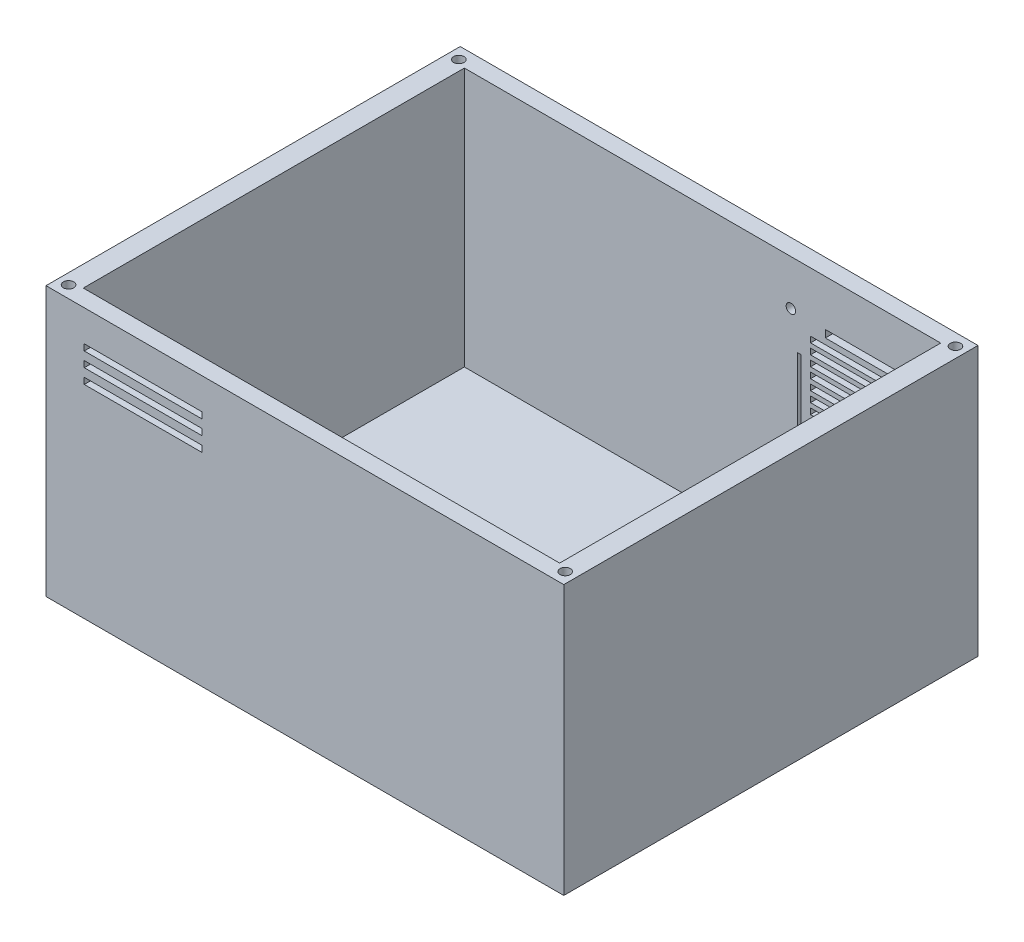
SolidWorks part; units mm, degrees
ref_plane "Front Plane" through (0, 0, 0) normal (0, 0, 1) x (1, 0, 0)
ref_plane "Top Plane" through (0, 0, 0) normal (0, 1, 0) x (1, 0, 0)
ref_plane "Right Plane" through (0, 0, 0) normal (1, 0, 0) x (0, 0, -1)
sketch "Sketch1" plane through (0, 0, 0) normal (0, 1, 0) x (1, 0, 0)
  line L1 (125, 100) -> (-125, 100)
  line L2 (125, 100) -> (125, -100)
  line L3 (125, -100) -> (-125, -100)
  line L4 (-125, 100) -> (-125, -100)
  line L5 (125, 100) -> (-125, -100) construction
  line L6 (125, -100) -> (-125, 100) construction
  line L7 (115, -92) -> (-115, -92)
  line L8 (115, -92) -> (115, 92)
  line L9 (115, 92) -> (-115, 92)
  line L10 (-115, -92) -> (-115, 92)
  line L11 (115, -92) -> (-115, 92) construction
  line L12 (115, 92) -> (-115, -92) construction
  point P0 (0, 0)
  point P6 (0, 0)
  dimension "D1" = 250
  dimension "D2" = 200
  dimension "D3" = 230
extrude "Boss-Extrude1" add sketch "Sketch1" along normal blind 125
sketch "Sketch2" plane through (0, 0, 0) normal (0, 1, 0) x (1, 0, 0)
  line L1 (-125, 100) -> (125, 100)
  line L2 (-125, 100) -> (-125, -100)
  line L3 (-125, -100) -> (125, -100)
  line L4 (125, 100) -> (125, -100)
extrude "Boss-Extrude2" add sketch "Sketch2" against normal blind 5
sketch "Sketch3" plane through (0, 125, 0) normal (0, 1, 0) x (1, 0, 0)
  line L0 (0, 0) -> (0, 92) construction
  line L1 (115, 92) -> (-115, 92) construction
  line L2 (0, 0) -> (-125, 0) construction
  line L3 (-125, 100) -> (-125, -100) construction
  circle A0 centre (-119.9007, -94.2189) radius 2.5
  circle A1 centre (-119.9007, 94.2189) radius 2.5
  circle A2 centre (119.9007, 94.2189) radius 2.5
  circle A3 centre (119.9007, -94.2189) radius 2.5
  dimension "D1" = 5
extrude "Cut-Extrude1" cut sketch "Sketch3" against normal blind 5
sketch "Sketch4" plane through (0, 0, 100) normal (0, 0, 1) x (1, 0, 0)
  line L1 (-106.5358, 109.9222) -> (-49.6477, 109.9222)
  line L2 (-106.5358, 109.9222) -> (-106.5358, 106.9222)
  line L3 (-106.5358, 106.9222) -> (-49.6477, 106.9222)
  line L4 (-49.6477, 109.9222) -> (-49.6477, 106.9222)
  line L5 (-106.5358, 102.9222) -> (-49.6477, 102.9222)
  line L6 (-106.5358, 102.9222) -> (-106.5358, 99.9222)
  line L7 (-106.5358, 99.9222) -> (-49.6477, 99.9222)
  line L8 (-49.6477, 102.9222) -> (-49.6477, 99.9222)
  line L9 (-106.5358, 95.9222) -> (-49.6477, 95.9222)
  line L10 (-106.5358, 95.9222) -> (-106.5358, 92.9222)
  line L11 (-106.5358, 92.9222) -> (-49.6477, 92.9222)
  line L12 (-49.6477, 95.9222) -> (-49.6477, 92.9222)
  dimension "D1" = 4
  dimension "D2" = 4
  dimension "D3" = 3
  dimension "D4" = 3
  dimension "D5" = 3
extrude "Cut-Extrude2" cut sketch "Sketch4" against normal blind 10
sketch "Sketch5" plane through (0, 0, -100) normal (0, 0, -1) x (-1, 0, 0)
  line L0 (-113.6581, 32.2575) -> (-42.6569, 103.2575) construction
  line L3 (-125, 67.7575) -> (125, 67.7575) construction
  line L4 (-125, 125) -> (-125, -5) construction
  line L5 (125, 125) -> (125, -5) construction
  circle A1 centre (-42.6569, 32.2575) radius 2.28
  circle A2 centre (-113.6581, 103.2575) radius 2.28
  circle A3 centre (-42.6569, 103.2575) radius 2.28
  circle A4 centre (-113.6581, 32.2575) radius 2.28
  point P0 (0, 0)
  dimension "D1" = 4.56
  dimension "D2" = 100.41
  dimension "D3" = 71
  dimension "D4" = 71
extrude "Cut-Extrude3" cut sketch "Sketch5" against normal blind 10
sketch "Sketch6" plane through (0, 0, -100) normal (0, 0, -1) x (-1, 0, 0)
  line L0 (-113.6581, 103.2575) -> (-42.6569, 32.2575) construction
  line L1 (-113.6581, 32.2575) -> (-42.6569, 103.2575) construction
  line L14 (-104.042, 88.6415) -> (-104.042, 91.4547)
  line L15 (-104.042, 93.6415) -> (-52.1185, 93.6415)
  line L16 (-104.042, 93.6415) -> (-104.042, 96.4547)
  line L17 (-104.042, 96.4547) -> (-52.1185, 96.4547)
  line L18 (-52.1185, 93.6415) -> (-52.1185, 96.4547)
  line L19 (-104.042, 88.6415) -> (-52.1185, 88.6415)
  line L20 (-52.1185, 88.6415) -> (-52.1185, 91.4547)
  line L21 (-104.042, 91.4547) -> (-52.1185, 91.4547)
  line L22 (-104.042, 83.6415) -> (-104.042, 86.4547)
  line L23 (-104.042, 83.6415) -> (-52.1185, 83.6415)
  line L24 (-52.1185, 83.6415) -> (-52.1185, 86.4547)
  line L25 (-104.042, 86.4547) -> (-52.1185, 86.4547)
  line L26 (-104.042, 78.6415) -> (-104.042, 81.4547)
  line L27 (-104.042, 78.6415) -> (-52.1185, 78.6415)
  line L28 (-52.1185, 78.6415) -> (-52.1185, 81.4547)
  line L29 (-104.042, 81.4547) -> (-52.1185, 81.4547)
  line L30 (-104.042, 73.6415) -> (-104.042, 76.4547)
  line L31 (-104.042, 73.6415) -> (-52.1185, 73.6415)
  line L32 (-52.1185, 73.6415) -> (-52.1185, 76.4547)
  line L33 (-104.042, 76.4547) -> (-52.1185, 76.4547)
  line L34 (-104.042, 68.6415) -> (-104.042, 71.4547)
  line L35 (-104.042, 68.6415) -> (-52.1185, 68.6415)
  line L36 (-52.1185, 68.6415) -> (-52.1185, 71.4547)
  line L37 (-104.042, 71.4547) -> (-52.1185, 71.4547)
  line L38 (-104.042, 63.6415) -> (-104.042, 66.4547)
  line L39 (-104.042, 63.6415) -> (-52.1185, 63.6415)
  line L40 (-52.1185, 63.6415) -> (-52.1185, 66.4547)
  line L41 (-104.042, 66.4547) -> (-52.1185, 66.4547)
  line L42 (-104.042, 58.6415) -> (-104.042, 61.4547)
  line L43 (-104.042, 58.6415) -> (-52.1185, 58.6415)
  line L44 (-52.1185, 58.6415) -> (-52.1185, 61.4547)
  line L45 (-104.042, 61.4547) -> (-52.1185, 61.4547)
  line L46 (-104.042, 53.6415) -> (-104.042, 56.4547)
  line L47 (-104.042, 53.6415) -> (-52.1185, 53.6415)
  line L48 (-52.1185, 53.6415) -> (-52.1185, 56.4547)
  line L49 (-104.042, 56.4547) -> (-52.1185, 56.4547)
  line L50 (-104.042, 48.6415) -> (-104.042, 51.4547)
  line L51 (-104.042, 48.6415) -> (-52.1185, 48.6415)
  line L52 (-52.1185, 48.6415) -> (-52.1185, 51.4547)
  line L53 (-104.042, 51.4547) -> (-52.1185, 51.4547)
  line L54 (-104.042, 43.6415) -> (-104.042, 46.4547)
  line L55 (-104.042, 43.6415) -> (-52.1185, 43.6415)
  line L56 (-52.1185, 43.6415) -> (-52.1185, 46.4547)
  line L57 (-104.042, 46.4547) -> (-52.1185, 46.4547)
  line L58 (-104.042, 38.6415) -> (-104.042, 41.4547)
  line L59 (-104.042, 38.6415) -> (-52.1185, 38.6415)
  line L60 (-52.1185, 38.6415) -> (-52.1185, 41.4547)
  line L61 (-104.042, 41.4547) -> (-52.1185, 41.4547)
  line L62 (-78.1575, 106.5075) -> (-78.1575, 29.0075) construction
  line L63 (-110.5591, 46.5042) -> (-108.853, 46.5042)
  line L64 (-110.5591, 46.5042) -> (-110.5591, 86.4547)
  line L65 (-110.5591, 86.4547) -> (-108.853, 86.4547)
  line L66 (-108.853, 46.5042) -> (-108.853, 86.4547)
  line L67 (-45.7559, 86.4547) -> (-47.462, 86.4547)
  line L68 (-47.462, 46.5042) -> (-47.462, 86.4547)
  line L69 (-45.7559, 46.5042) -> (-47.462, 46.5042)
  line L70 (-45.7559, 46.5042) -> (-45.7559, 86.4547)
  line L71 (-116.9075, 67.7575) -> (-39.4075, 67.7575) construction
  line L72 (-94.6213, 102.836) -> (-59.3099, 102.836)
  line L73 (-94.6213, 102.836) -> (-94.6213, 99.2832)
  line L74 (-94.6213, 99.2832) -> (-59.3099, 99.2832)
  line L75 (-59.3099, 102.836) -> (-59.3099, 99.2832)
  line L76 (-94.6213, 36.2317) -> (-59.3099, 36.2317)
  line L77 (-59.3099, 32.6789) -> (-59.3099, 36.2317)
  line L78 (-94.6213, 32.6789) -> (-59.3099, 32.6789)
  line L79 (-94.6213, 32.6789) -> (-94.6213, 36.2317)
  circle A0 centre (-78.1575, 67.7575) radius 38.75 construction
  dimension "D1" = 12
extrude "Cut-Extrude4" cut sketch "Sketch6" against normal blind 10
